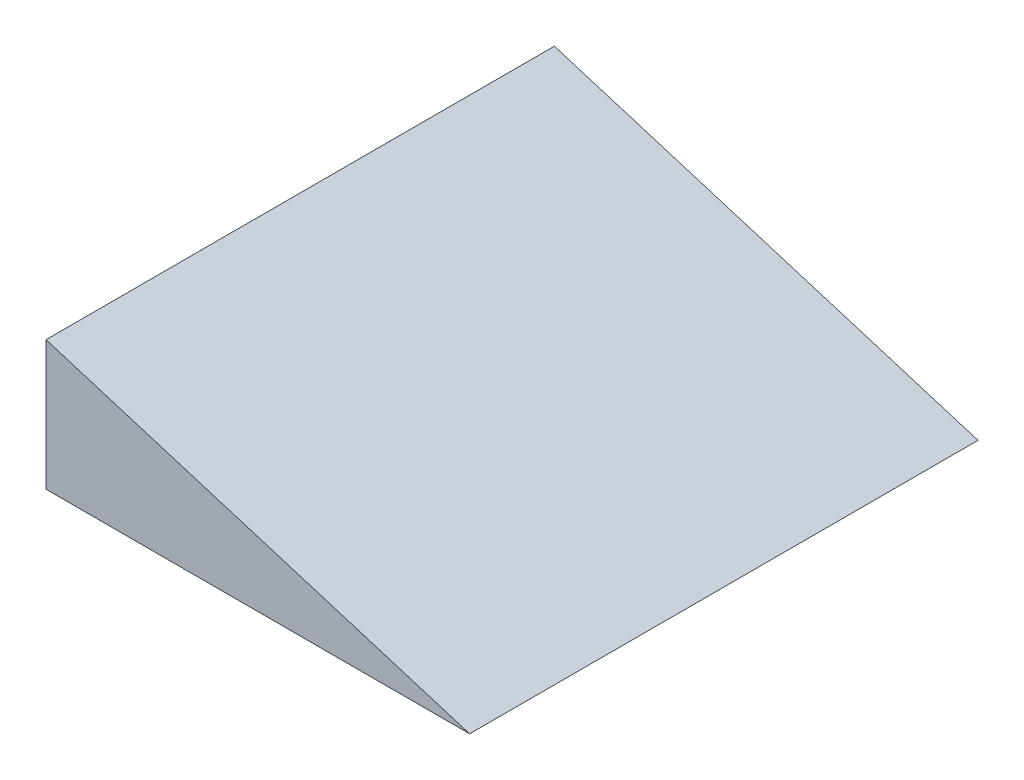
SolidWorks part; units mm, degrees
ref_plane "前视基准面" through (0, 0, 0) normal (0, 0, 1) x (1, 0, 0)
ref_plane "上视基准面" through (0, 0, 0) normal (0, 1, 0) x (1, 0, 0)
ref_plane "右视基准面" through (0, 0, 0) normal (1, 0, 0) x (0, 0, -1)
sketch "草图1" plane through (0, 0, 0) normal (0, 0, 1) x (1, 0, 0)
  line L0 (0, 0) -> (-500, 0)
  line L1 (-500, 0) -> (-500, 152.8653)
  line L2 (-500, 152.8653) -> (0, 0)
  dimension "D1" = 500
  dimension "D2" = 17
extrude "凸台-拉伸1" add sketch "草图1" against normal blind 600
